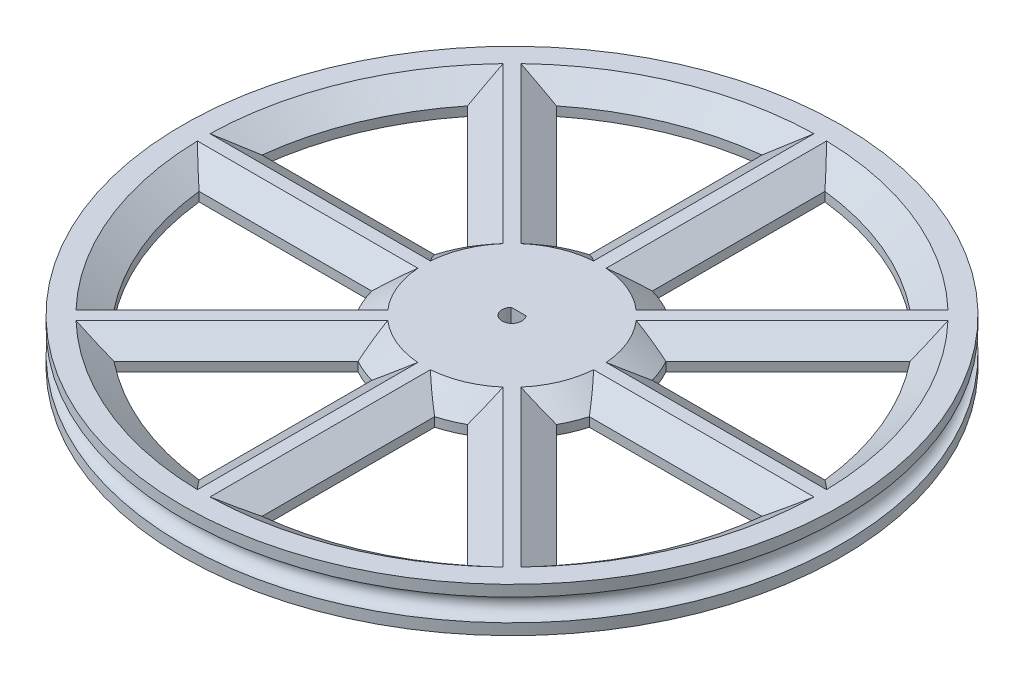
SolidWorks part; units mm, degrees
ref_plane "前视基准面" through (0, 0, 0) normal (0, 0, 1) x (1, 0, 0)
ref_plane "上视基准面" through (0, 0, 0) normal (0, 1, 0) x (1, 0, 0)
ref_plane "右视基准面" through (0, 0, 0) normal (1, 0, 0) x (0, 0, -1)
sketch "Sketch1" plane through (0, 0, 0) normal (0, 1, 0) x (1, 0, 0)
  circle A0 centre (0, 0) radius 52.3621
  dimension "D1" = 104.7242
extrude "Boss-Extrude1" add sketch "Sketch1" along normal blind 7.06
sketch "Sketch4" plane through (0, 0, 0) normal (1, 0, 0) x (0, 0, -1)
  line L0 (-52.3621, 7.06) -> (-52.3621, 0) construction
  circle A0 centre (-52.3621, 3.53) radius 1.7653
  dimension "D1" = 3.5306
revolve "Cut-Revolve2" cut sketch "Sketch4" angle 360 about L0
sketch "Sketch6" plane through (0, 7.06, 0) normal (0, 1, 0) x (1, 0, 0)
  circle A0 centre (0, 0) radius 1.575
  dimension "D1" = 3.15
extrude "Cut-Extrude1" cut sketch "Sketch6" against normal blind 7.06
sketch "Sketch7" plane through (0, 7.06, 0) normal (0, 1, 0) x (1, 0, 0)
  line L0 (-1.8875, 1.05) -> (2.4111, 1.05) construction
  line L1 (-1.1739, 1.05) -> (1.1739, 1.05)
  arc A0 (1.1739, 1.05) -> (-1.1739, 1.05) centre (0, 0) ccw
  circle A1 centre (0, 0) radius 1.575 construction
  dimension "D1" = 1.05
extrude "Boss-Extrude2" add sketch "Sketch7" against normal blind 7.06
sketch "Sketch8" plane through (0, 7.06, 0) normal (0, 1, 0) x (1, 0, 0)
  line L0 (0, 0) -> (69.2248, 0) construction
  line L1 (0, 0) -> (0, 87.3853) construction
  line L2 (0, 0) -> (-74.6301, 0) construction
  line L3 (0, 0) -> (0, -92.3595) construction
  line L4 (0, 0) -> (64.1177, 64.1177) construction
  line L5 (0, 0) -> (-59.695, 59.695) construction
  line L6 (0, 0) -> (52.0905, -52.0905) construction
  line L7 (0, 0) -> (-50.6219, -50.6219) construction
  line L8 (-74.6301, -5) -> (69.2248, -5) construction
  line L9 (-74.6301, 5) -> (69.2248, 5) construction
  line L10 (-5, 87.3853) -> (-5, -81.2296) construction
  line L11 (5, 87.3853) -> (5, -81.2296) construction
  line L12 (-62.0922, 55.0211) -> (43.648, -50.719) construction
  line L13 (-56.289, 63.3601) -> (54.8796, -47.8085) construction
  line L14 (56.4776, 63.5487) -> (-51.1948, -44.1237) construction
  line L15 (-42.9749, -50.046) -> (64.19, 57.1189) construction
  line L16 (-44.7214, 5) -> (-17.2916, 5)
  line L17 (-15.7626, 8.6915) -> (-35.1583, 28.0872)
  line L18 (-17.2916, -5) -> (-44.7214, -5)
  line L19 (-35.1583, -28.0872) -> (-15.7626, -8.6915)
  line L20 (17.2916, -5) -> (44.7214, -5)
  line L21 (15.7626, 8.6915) -> (35.1583, 28.0872)
  line L22 (15.7626, -8.6915) -> (35.1583, -28.0872)
  line L23 (-28.0872, 35.1583) -> (-8.6915, 15.7626)
  line L24 (-5, 17.2916) -> (-5, 44.7214)
  line L25 (5, 17.2916) -> (5, 44.7214)
  line L26 (-28.0872, -35.1583) -> (-8.6915, -15.7626)
  line L27 (-5, -17.2916) -> (-5, -44.7214)
  line L28 (5, -17.2916) -> (5, -44.7214)
  line L29 (8.6915, -15.7626) -> (28.0872, -35.1583)
  line L30 (8.6915, 15.7626) -> (28.0872, 35.1583)
  line L31 (17.2916, 5) -> (44.7214, 5)
  arc A0 (-15.7626, 8.6915) -> (-17.2916, 5) centre (0, 0) ccw
  arc A1 (-35.1583, 28.0872) -> (-44.7214, 5) centre (0, 0) ccw
  arc A2 (-17.2916, -5) -> (-15.7626, -8.6915) centre (0, 0) ccw
  arc A3 (-44.7214, -5) -> (-35.1583, -28.0872) centre (0, 0) ccw
  arc A4 (15.7626, 8.6915) -> (17.2916, 5) centre (0, 0) cw
  arc A5 (35.1583, 28.0872) -> (44.7214, 5) centre (0, 0) cw
  arc A6 (17.2916, -5) -> (15.7626, -8.6915) centre (0, 0) cw
  arc A7 (44.7214, -5) -> (35.1583, -28.0872) centre (0, 0) cw
  arc A8 (-8.6915, -15.7626) -> (-5, -17.2916) centre (0, 0) ccw
  arc A9 (-28.0872, -35.1583) -> (-5, -44.7214) centre (0, 0) ccw
  arc A10 (5, -17.2916) -> (8.6915, -15.7626) centre (0, 0) ccw
  arc A11 (5, -44.7214) -> (28.0872, -35.1583) centre (0, 0) ccw
  arc A12 (8.6915, 15.7626) -> (5, 17.2916) centre (0, 0) ccw
  arc A13 (-5, 17.2916) -> (-8.6915, 15.7626) centre (0, 0) ccw
  arc A14 (28.0872, 35.1583) -> (5, 44.7214) centre (0, 0) ccw
  arc A15 (-5, 44.7214) -> (-28.0872, 35.1583) centre (0, 0) ccw
  point P27 (-35.1583, 28.0872)
  point P28 (-15.7626, 8.6915)
  point P33 (-44.7214, -5)
  point P34 (-17.2916, -5)
  point P35 (15.7626, 8.6915)
  point P36 (35.1583, 28.0872)
  point P49 (-8.6915, -15.7626)
  point P50 (-28.0872, -35.1583)
  dimension "D1" = 5
  dimension "D2" = 5
  dimension "D3" = 5
  dimension "D4" = 5
  dimension "D5" = 5
  dimension "D6" = 5
  dimension "D7" = 5
  dimension "D8" = 5
  dimension "D9" = 45
  dimension "D10" = 18
  dimension "D11" = 18
  dimension "D12" = 45
extrude "Cut-Extrude3" cut sketch "Sketch8" against normal blind 7.06
chamfer "Chamfer17" distance 4 angle 35 2 edges at (-25.4604, 7.06, -18.3894) (-18.3894, 7.06, -25.4604)
chamfer "Chamfer18" distance 4 angle 35 1 edges at (-18.3894, 0, -25.4604)
chamfer "Chamfer19" distance 4 angle 35 1 edges at (-25.4604, 0, -18.3894)
chamfer "Chamfer20" distance 4 angle 35 2 edges at (-31.0065, 7.06, 5) (-31.0065, 7.06, -5)
chamfer "Chamfer21" distance 4 angle 35 12 edges at (-5, 7.06, -31.0065) (5, 7.06, -31.0065) (18.3894, 7.06, -25.4604) (25.4604, 7.06, -18.3894) (31.0065, 7.06, -5) (31.0065, 7.06, 5) (25.4604, 7.06, 18.3894) (18.3894, 7.06, 25.4604) (5, 7.06, 31.0065) (-5, 7.06, 31.0065) (-18.3894, 7.06, 25.4604) (-25.4604, 7.06, 18.3894)
chamfer "Chamfer25" distance 4 angle 35 2 edges at (5, 0, -31.0065) (-5, 0, -31.0065)
chamfer "Chamfer26" distance 4 angle 35 6 edges at (18.3894, 0, 25.4604) (25.4604, 0, 18.3894) (31.0065, 0, 5) (31.0065, 0, -5) (25.4604, 0, -18.3894) (18.3894, 0, -25.4604)
chamfer "Chamfer39" distance 4 angle 35 1 edges at (16.6298, 0, 6.8883)
chamfer "Chamfer40" distance 4 angle 35 9 edges at (16.6298, 0, -6.8883) (6.8883, 0, -16.6298) (-6.8883, 0, -16.6298) (-31.0065, 0, -5) (-31.0065, 0, 5) (-25.4604, 0, 18.3894) (-18.3894, 0, 25.4604) (-5, 0, 31.0065) (5, 0, 31.0065)
chamfer "Chamfer42" distance 4 angle 35 4 edges at (-16.6298, 0, -6.8883) (-16.6298, 0, 6.8883) (-6.8883, 0, 16.6298) (6.8883, 0, 16.6298)
chamfer "Chamfer43" distance 4 angle 35 8 edges at (-6.8883, 7.06, -16.6298) (6.8883, 7.06, -16.6298) (16.6298, 7.06, -6.8883) (16.6298, 7.06, 6.8883) (6.8883, 7.06, 16.6298) (-6.8883, 7.06, 16.6298) (-16.6298, 7.06, 6.8883) (-16.6298, 7.06, -6.8883)
chamfer "Chamfer44" distance 4 angle 35 1 edges at (41.5746, 0, -17.2208)
chamfer "Chamfer45" distance 4 angle 35 7 edges at (17.2208, 0, -41.5746) (-17.2208, 0, -41.5746) (-41.5746, 0, -17.2208) (-41.5746, 0, 17.2208) (-17.2208, 0, 41.5746) (17.2208, 0, 41.5746) (41.5746, 0, 17.2208)
chamfer "Chamfer46" distance 4 angle 35 8 edges at (-41.5746, 7.06, 17.2208) (-17.2208, 7.06, 41.5746) (17.2208, 7.06, 41.5746) (41.5746, 7.06, 17.2208) (41.5746, 7.06, -17.2208) (17.2208, 7.06, -41.5746) (-17.2208, 7.06, -41.5746) (-41.5746, 7.06, -17.2208)
